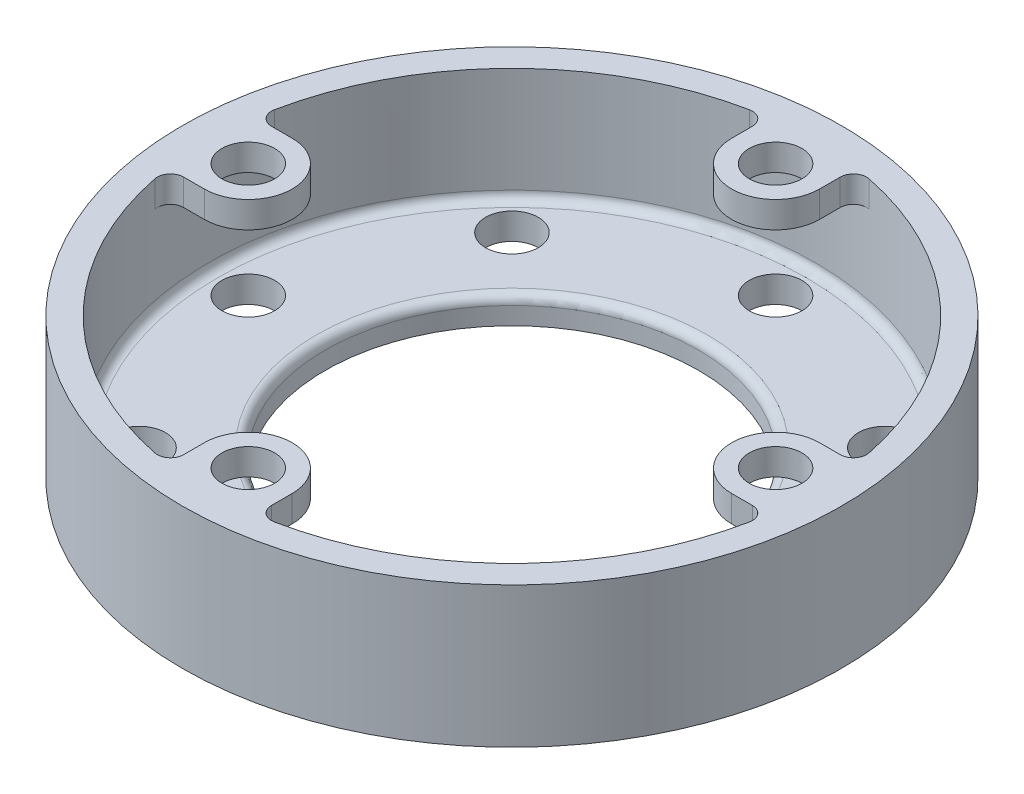
SolidWorks part; units mm, degrees
material "PW20:29:Sc:0:"
ref_plane "Front" through (0, 0, 0) normal (0, 0, 1) x (1, 0, 0)
ref_plane "Top" through (0, 0, 0) normal (0, 1, 0) x (1, 0, 0)
ref_plane "Right" through (0, 0, 0) normal (1, 0, 0) x (0, 0, -1)
sketch "Sketch1" plane through (0, 0, 0) normal (0, 1, 0) x (1, 0, 0)
  circle A0 centre (0, 0) radius 75
  dimension "D1" = 150
extrude "Base-Extrude" add sketch "Sketch1" along normal blind 32
shell "Shell1" thickness 6
sketch "Sketch4" plane through (0, 6, 0) normal (0, 1, 0) x (-1, 0, 0)
  circle A0 centre (0, 0) radius 42.5
  dimension "D1" = 85
extrude "Cut-Extrude2" cut sketch "Sketch4" against normal through all
sketch "Sketch2" plane through (0, 32, 0) normal (0, 1, 0) x (-1, 0, 0)
  line L0 (0, -75) -> (0, 75) construction
  line L1 (-10, -68.2715) -> (-10, -60)
  line L2 (10, -60) -> (10, -68.2715)
  circle A0 centre (0, 0) radius 75 construction
  arc A1 (-10, -68.2715) -> (10, -68.2715) centre (0, 0) ccw
  circle A2 centre (0, 0) radius 69 construction
  arc A3 (-10, -60) -> (10, -60) centre (0, -60) cw
  dimension "D2" = 10
  dimension "D1" = 60
extrude "Boss-Extrude1" add sketch "Sketch2" against normal blind 6
sketch "Sketch3" plane through (0, 32, 0) normal (0, 1, 0) x (-1, 0, 0)
  circle A0 centre (0, -60) radius 6
  arc A2 (10, -60) -> (-10, -60) centre (0, -60) ccw construction
  dimension "D1" = 12
extrude "Cut-Extrude1" cut sketch "Sketch3" against normal up to next
fillet "Fillet1" radius 3 2 edges at (-10, 29, -68.2715) (10, 29, -68.2715)
pattern_circular "CirPattern1" count 4 every 90 about axis through (0, 0, 0) along (0, 1, 0) of "Fillet1", "Boss-Extrude1", "Cut-Extrude1"
sketch "Sketch5" plane through (0, 6, 0) normal (0, 1, 0) x (-1, 0, 0)
  circle A0 centre (0, -60) radius 6 construction
  circle A1 centre (0, -60) radius 6
extrude "Cut-Extrude3" cut sketch "Sketch5" against normal through all
pattern_circular "CirPattern2" count 8 every 45 about axis through (0, 0, 0) along (0, 1, 0) of "Cut-Extrude3"
fillet "Fillet2" radius 2 2 edges at (0, 6, 69) (0, 6, 42.5)
